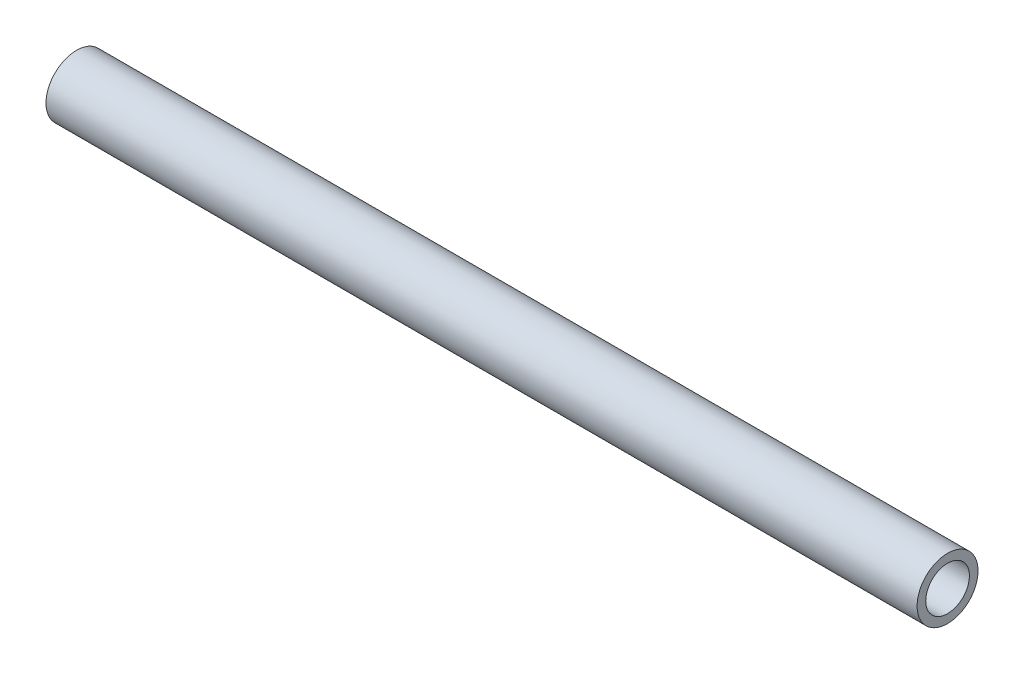
SolidWorks part; units mm, degrees
ref_plane "Front Plane" through (0, 0, 0) normal (0, 0, 1) x (1, 0, 0)
ref_plane "Top Plane" through (0, 0, 0) normal (0, 1, 0) x (1, 0, 0)
ref_plane "Right Plane" through (0, 0, 0) normal (1, 0, 0) x (0, 0, -1)
sketch "Sketch1" plane through (0, 0, 0) normal (1, 0, 0) x (0, 0, -1)
  circle A0 centre (0, 0) radius 7.6454
  circle A1 centre (0, 0) radius 10.668
extrude "Boss-Extrude1" add sketch "Sketch1" along normal blind 304.8
